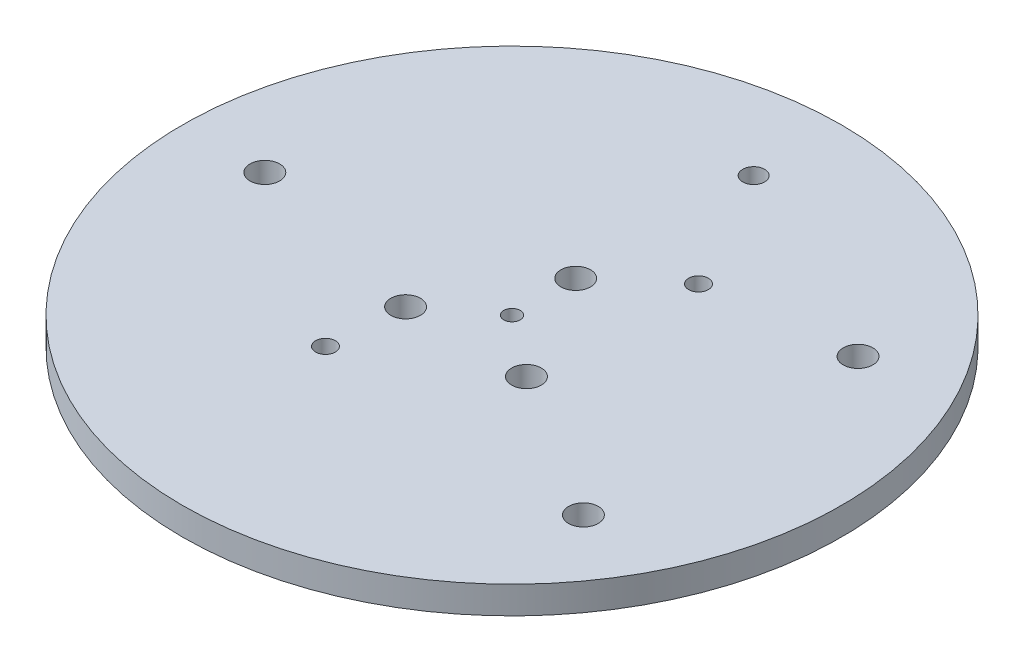
SolidWorks part; units mm, degrees
material "AISI 304"
ref_plane "Front Plane" through (0, 0, 0) normal (0, 0, 1) x (1, 0, 0)
ref_plane "Top Plane" through (0, 0, 0) normal (0, 1, 0) x (1, 0, 0)
ref_plane "Right Plane" through (0, 0, 0) normal (1, 0, 0) x (0, 0, -1)
sketch "Sketch1" plane through (0, 0, 0) normal (0, 1, 0) x (1, 0, 0)
  circle A0 centre (0, 0) radius 76.2
  dimension "D1" = 152.4
extrude "Boss-Extrude1" add sketch "Sketch1" along normal blind 6.35
sketch "Sketch2" plane through (0, 6.35, 0) normal (0, 1, 0) x (1, 0, 0)
  circle A0 centre (0, 0) radius 1.905
  dimension "D1" = 3.81
extrude "Cut-Extrude1" cut sketch "Sketch2" against normal through all
sketch "Sketch3" plane through (0, 6.35, 0) normal (0, 1, 0) x (1, 0, 0)
  circle A0 centre (0, 14.732) radius 3.429
  circle A1 centre (-13.97, -10.6311) radius 3.429
  circle A2 centre (13.97, -10.6311) radius 3.429
  dimension "D4" = 6.858
  dimension "D5" = 6.858
  dimension "D6" = 6.858
  dimension "D1" = 14.732
  dimension "D2" = 13.97
  dimension "D3" = 13.97
  dimension "D7" = 28.956
  dimension "D8" = 28.956
  dimension "D9" = 27.94
extrude "Cut-Extrude2" cut sketch "Sketch3" against normal through all
sketch "Sketch4" plane through (0, 6.35, 0) normal (0, 1, 0) x (1, 0, 0)
  line L1 (48.26, 31.75) -> (48.26, -31.75)
  circle A0 centre (-57.15, 0) radius 3.429
  circle A1 centre (0, 0) radius 1.905 construction
  circle A2 centre (-13.97, -10.6311) radius 3.429 construction
  circle A4 centre (48.26, 31.75) radius 3.429
  circle A5 centre (48.26, -31.75) radius 3.429
  dimension "D1" = 6.858
  dimension "D2" = 57.15
  dimension "D3" = 48.26
  dimension "D6" = 43.18
  dimension "D7" = 6.858
  dimension "D8" = 6.858
  dimension "D4" = 63.5
  dimension "D5" = 31.75
extrude "Cut-Extrude3" cut sketch "Sketch4" against normal through all
sketch "Sketch5" plane through (0, 6.35, 0) normal (0, 1, 0) x (1, 0, 0)
  circle A0 centre (0, 55.88) radius 2.54
  circle A1 centre (0, 0) radius 1.905 construction
  circle A2 centre (48.26, 31.75) radius 3.429 construction
  dimension "D1" = 5.08
  dimension "D2" = 55.88
  dimension "D3" = 48.26
extrude "Cut-Extrude4" cut sketch "Sketch5" against normal through all
sketch "Sketch6" plane through (0, 6.35, 0) normal (0, 1, 0) x (1, 0, 0)
  line L1 (28.2633, 51.347) -> (-24.3266, -44.1951)
  circle A3 centre (15.3103, 27.8147) radius 2.286
  circle A4 centre (-15.3103, -27.8147) radius 2.286
  circle A5 centre (-13.97, -10.6311) radius 3.429 construction
  dimension "D1" = 7.112
  dimension "D2" = 31.75
  dimension "D3" = 4.572
  dimension "D4" = 4.572
  dimension "D5" = 31.75
extrude "Cut-Extrude5" cut sketch "Sketch6" against normal through all contours L1 A4 | L1 A4 | L1 A3 | L1 A3
